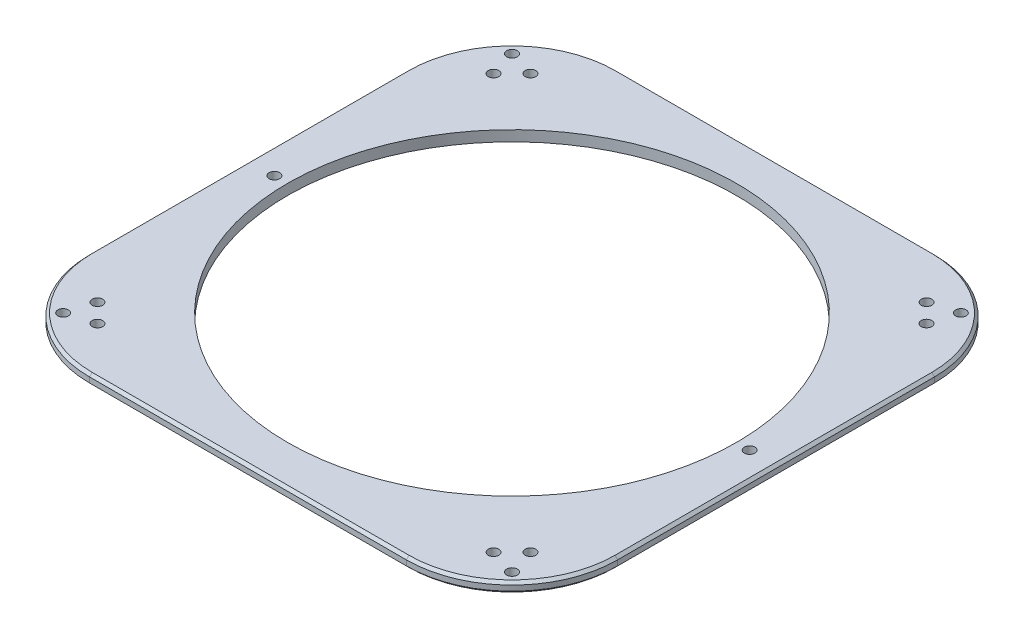
SolidWorks part; units mm, degrees
ref_plane "Спереди" through (0, 0, 0) normal (0, 0, 1) x (1, 0, 0)
ref_plane "Сверху" through (0, 0, 0) normal (0, 1, 0) x (1, 0, 0)
ref_plane "Справа" through (0, 0, 0) normal (1, 0, 0) x (0, 0, -1)
sketch "Эскиз1" plane through (0, 0, 0) normal (0, 1, 0) x (1, 0, 0)
  line L1 (-100, -100) -> (100, -100)
  line L2 (-100, -100) -> (-100, 100)
  line L3 (-100, 100) -> (100, 100)
  line L4 (100, -100) -> (100, 100)
  line L5 (0, 100) -> (0, -100) construction
  line L6 (-100, 0) -> (100, 0) construction
  line L7 (-85, -85) -> (85, -85) construction
  line L8 (-85, -85) -> (-85, 85) construction
  line L9 (-85, 85) -> (85, 85) construction
  line L10 (85, -85) -> (85, 85) construction
  line L11 (0, 85) -> (0, -85) construction
  line L12 (-85, 0) -> (85, 0) construction
  line L13 (-75, -82) -> (75, -82) construction
  line L14 (-75, -82) -> (-75, 82) construction
  line L15 (-75, 82) -> (75, 82) construction
  line L16 (75, -82) -> (75, 82) construction
  line L17 (0, 82) -> (0, -82) construction
  line L18 (-75, 0) -> (75, 0) construction
  line L19 (-82, -75) -> (82, -75) construction
  line L20 (-82, -75) -> (-82, 75) construction
  line L21 (-82, 75) -> (82, 75) construction
  line L22 (82, -75) -> (82, 75) construction
  line L23 (0, 75) -> (0, -75) construction
  line L24 (-82, 0) -> (82, 0) construction
  circle A0 centre (-85, 85) radius 2
  circle A1 centre (85, 85) radius 2
  circle A2 centre (85, -85) radius 2
  circle A3 centre (-85, -85) radius 2
  circle A4 centre (-90, 0) radius 2
  circle A5 centre (90, 0) radius 2
  circle A6 centre (75, 82) radius 2
  circle A7 centre (-75, 82) radius 2
  circle A8 centre (75, -82) radius 2
  circle A9 centre (-75, -82) radius 2
  circle A10 centre (82, -75) radius 2
  circle A11 centre (-82, -75) radius 2
  circle A12 centre (-82, 75) radius 2
  circle A13 centre (81.9873, 75.0019) radius 2
  circle A14 centre (0, 0) radius 85
  point P0 (0, 0)
  point P4 (0, 0)
  point P11 (0, 0)
  point P20 (0, 0)
  dimension "D3" = 90
  dimension "D8" = 170
  dimension "D1" = 200
  dimension "D2" = 170
  dimension "D4" = 150
  dimension "D5" = 164
  dimension "D6" = 150
  dimension "D7" = 164
extrude "Бобышка-Вытянуть1" add sketch "Эскиз1" along normal blind 4
fillet "Скругление1" radius 40 4 edges at (-100, 2, -100) (-100, 2, 100) (100, 2, -100) (100, 2, 100)
chamfer "Фаска1" distance 1 angle 45 16 edges at (-100, 0, 0) (-88.2843, 0, 88.2843) (-88.2843, 0, -88.2843) (0, 0, 100) (0, 0, -100) (88.2843, 0, 88.2843) (88.2843, 0, -88.2843) (100, 0, 0) (-100, 4, 0) (-88.2843, 4, 88.2843) (-88.2843, 4, -88.2843) (0, 4, 100) (0, 4, -100) (88.2843, 4, 88.2843) (88.2843, 4, -88.2843) (100, 4, 0)
